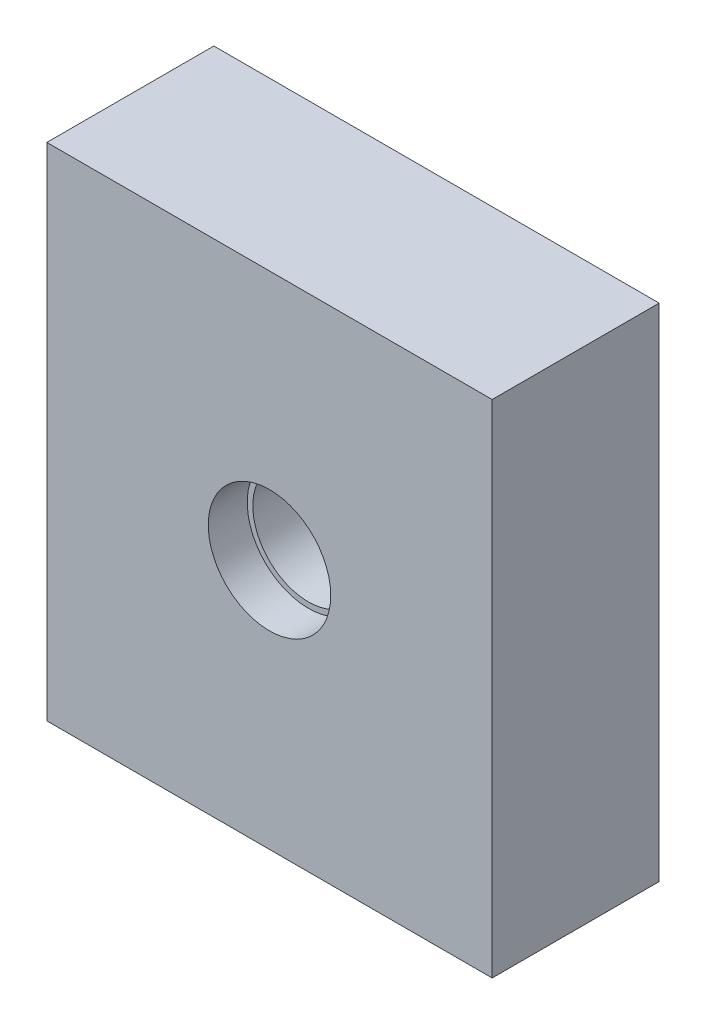
SolidWorks part; units mm, degrees
material "5052-H32"
ref_plane "Front Plane" through (0, 0, 0) normal (0, 0, 1) x (1, 0, 0)
ref_plane "Top Plane" through (0, 0, 0) normal (0, 1, 0) x (1, 0, 0)
ref_plane "Right Plane" through (0, 0, 0) normal (1, 0, 0) x (0, 0, -1)
ref_plane "Plane1" through (0, 0, 0) normal (0, 0, -1) x (-1, 0, 0)
sketch "Sketch1" plane through (0, 0, 0) normal (0, 0, -1) x (-1, 0, 0)
  line L0 (0, 90) -> (-80, 90)
  line L1 (-80, 90) -> (-80, 0)
  line L2 (-80, 0) -> (0, 0)
  line L3 (0, 0) -> (0, 90)
  dimension "D1" = 80
  dimension "D2" = 90
extrude "Boss-Extrude1" add sketch "Sketch1" against normal blind 30
ref_plane "Plane2" through (0, 45, 0) normal (0, -1, 0) x (-1, 0, 0)
sketch "Sketch2" plane through (0, 45, 0) normal (0, -1, 0) x (-1, 0, 0)
  line L0 (-29, 0) -> (-40, 0)
  line L1 (-40, 0) -> (-40, -30)
  line L2 (-40, -30) -> (-29, -30)
  line L3 (-29, -30) -> (-29, -23)
  line L4 (-29, -23) -> (-30, -23)
  line L5 (-30, -23) -> (-30, -8)
  line L6 (-30, -8) -> (-29, -8)
  line L7 (-29, -8) -> (-29, 0)
  line L8 (-40, 0) -> (-40, -30) construction
  line L9 (0, 0) -> (-80, 0) construction
  line L10 (-40, 0) -> (-40, -30) construction
  line L11 (0, -30) -> (-80, -30) construction
  dimension "D1" = 11
  dimension "D2" = 10
revolve "Cut-Revolve1" cut sketch "Sketch2" angle 360 about L8
hole_wizard "Ø2.5 (2.5) Diameter Hole1" positions "Sketch6" profile "Sketch5" hole size "Ø2.5" standard "ANSI Metric"
sketch "Sketch6" plane through (0, 0, 0) normal (0, 0, -1) x (-1, 0, 0)
  line L0 (-26.75, 63.7999) -> (-53.25, 26.2001) construction
  circle A0 centre (-40, 45) radius 23 construction
  point P0 (-26.75, 63.7999)
  point P1 (-53.25, 26.2001)
  dimension "D1" = 46
  dimension "D2" = 26.5
sketch "Sketch5" plane through (26.75, 63.7999, 0) normal (1, 0, 0) x (0, 1, 0)
  line L0 (0, 0) -> (0, 7.7217)
  line L1 (0, 7.7217) -> (1.25, 7)
  line L2 (1.25, 7) -> (1.25, 0)
  line L5 (1.25, 0) -> (0, 0)
  line L10 (0, 7.7217) -> (-1.25, 7) construction
  line L11 (0, -6.35) -> (0, 107.95) construction
  dimension "Hole Dia." = 2.5
  dimension "Hole Depth" = 7
  dimension "Drill Angle" = 120
hole_wizard "Ø8.0 (8) Diameter Hole1" positions "Sketch9" profile "Sketch8" hole size "Ø8.0" standard "ANSI Metric"
sketch "Sketch9" plane through (0, 0, 0) normal (0, 0, -1) x (-1, 0, 0)
  line L1 (0, 0) -> (0, 90) construction
  line L2 (-80, 0) -> (0, 0) construction
  line L3 (-80, 45) -> (0, 45) construction
  line L4 (-80, 90) -> (-80, 0) construction
  line L6 (-65, 10) -> (-30, 10) construction
  point P0 (-30, 10)
  point P19 (-30, 80)
  point P25 (-65, 10)
  point P31 (-65, 80)
  dimension "D1" = 30
  dimension "D2" = 35
  dimension "D3" = 10
sketch "Sketch8" plane through (30, 10, 0) normal (1, 0, 0) x (0, 1, 0)
  line L0 (0, 0) -> (0, 12.3094)
  line L1 (0, 12.3094) -> (4, 10)
  line L2 (4, 10) -> (4, 0)
  line L5 (4, 0) -> (0, 0)
  line L10 (0, 12.3094) -> (-4, 10) construction
  line L11 (0, -6.35) -> (0, 107.95) construction
  dimension "Hole Dia." = 8
  dimension "Hole Depth" = 10
  dimension "Drill Angle" = 120
